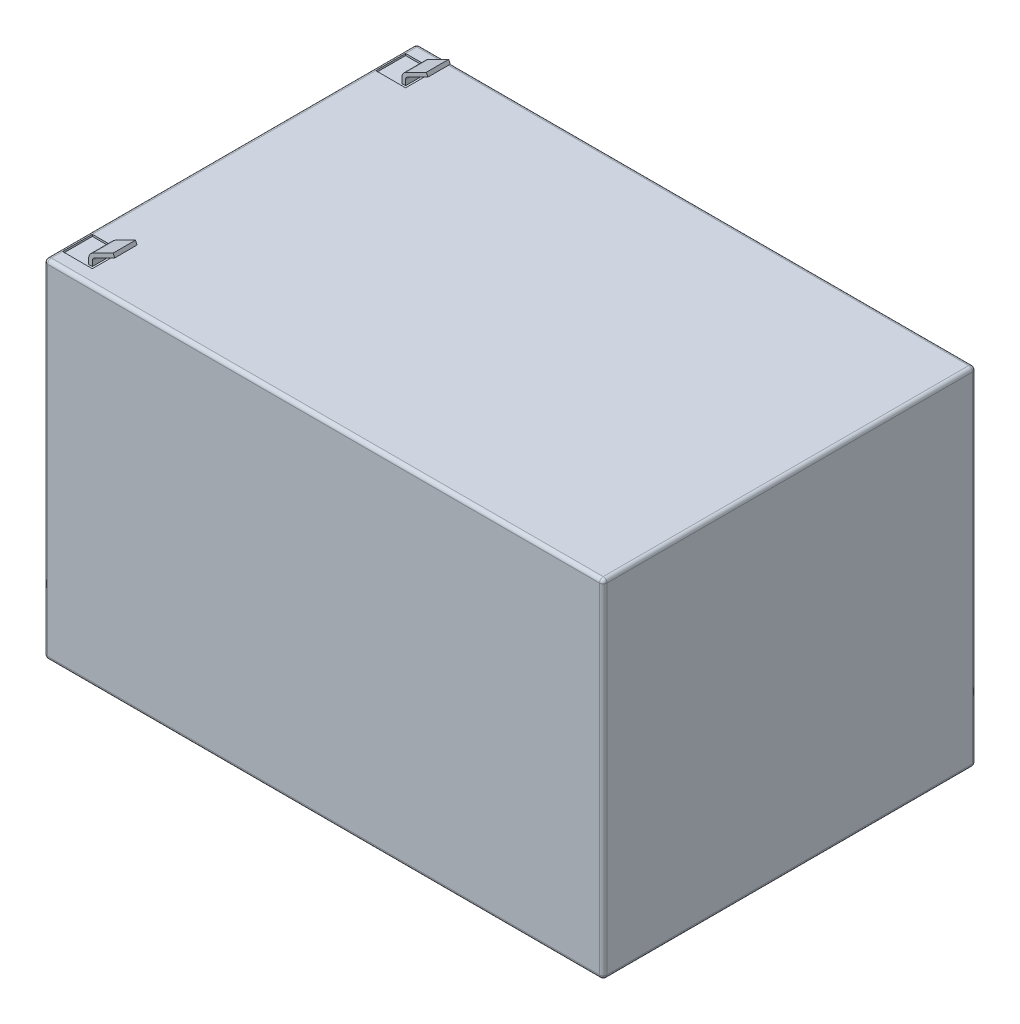
SolidWorks part; units mm, degrees
ref_plane "Front Plane" through (0, 0, 0) normal (0, 0, 1) x (1, 0, 0)
ref_plane "Top Plane" through (0, 0, 0) normal (0, 1, 0) x (1, 0, 0)
ref_plane "Right Plane" through (0, 0, 0) normal (1, 0, 0) x (0, 0, -1)
sketch "Sketch1" plane through (0, 0, 0) normal (0, 1, 0) x (1, 0, 0)
  line L1 (-75, -50) -> (75, -50)
  line L2 (-75, -50) -> (-75, 50)
  line L3 (-75, 50) -> (75, 50)
  line L4 (75, -50) -> (75, 50)
  line L5 (-75, -50) -> (75, 50) construction
  line L6 (-75, 50) -> (75, -50) construction
  point P0 (0, 0)
  dimension "D1" = 100
  dimension "D2" = 150
extrude "Boss-Extrude1" add sketch "Sketch1" along normal blind 93
fillet "Fillet1" radius 1 12 edges at (75, 46.5, -50) (-75, 46.5, -50) (-75, 46.5, 50) (75, 46.5, 50) (0, 93, 50) (-75, 93, 0) (0, 93, -50) (75, 93, 0) (0, 0, 50) (-75, 0, 0) (0, 0, -50) (75, 0, 0)
sketch "Sketch2" plane through (0, 93, 0) normal (0, 1, 0) x (1, 0, 0)
  line L0 (-74, 49) -> (-74, -49) construction
  line L1 (-74, 46) -> (-66, 46)
  line L2 (-74, 46) -> (-74, 38)
  line L3 (-74, 38) -> (-66, 38)
  line L4 (-66, 46) -> (-66, 38)
  line L5 (74, 49) -> (-74, 49) construction
  dimension "D1" = 8
  dimension "D2" = 8
  dimension "D3" = 3
extrude "Cut-Extrude1" cut sketch "Sketch2" against normal blind 0.5
mirror "Mirror1" about plane through (0, 0, 0) normal (0, 0, 1) of "Cut-Extrude1"
sketch "Sketch3" plane through (0, 0, -46) normal (0, 0, 1) x (1, 0, 0)
  line L0 (-67, 92.5) -> (-67, 93.8793)
  line L1 (-66, 92.5) -> (-74, 92.5) construction
  line L2 (-66.4472, 94.7738) -> (-61, 97.4974)
  line L3 (-66, 92.5) -> (-66, 93) construction
  arc A0 (-67, 93.8793) -> (-66.4472, 94.7738) centre (-66, 93.8793) cw
  point P7 (-67, 94.4974)
  dimension "D4" = 1
  dimension "D1" = 1.9974
  dimension "D2" = 6
  dimension "D3" = 3
  dimension "D5" = 1
extrude "Extrude-Thin1" add sketch "Sketch3" along normal blind 6 from offset 1 thin thin type one direction reverse wall 1
mirror "Mirror2" about plane through (0, 0, 0) normal (0, 0, 1) of "Extrude-Thin1"
